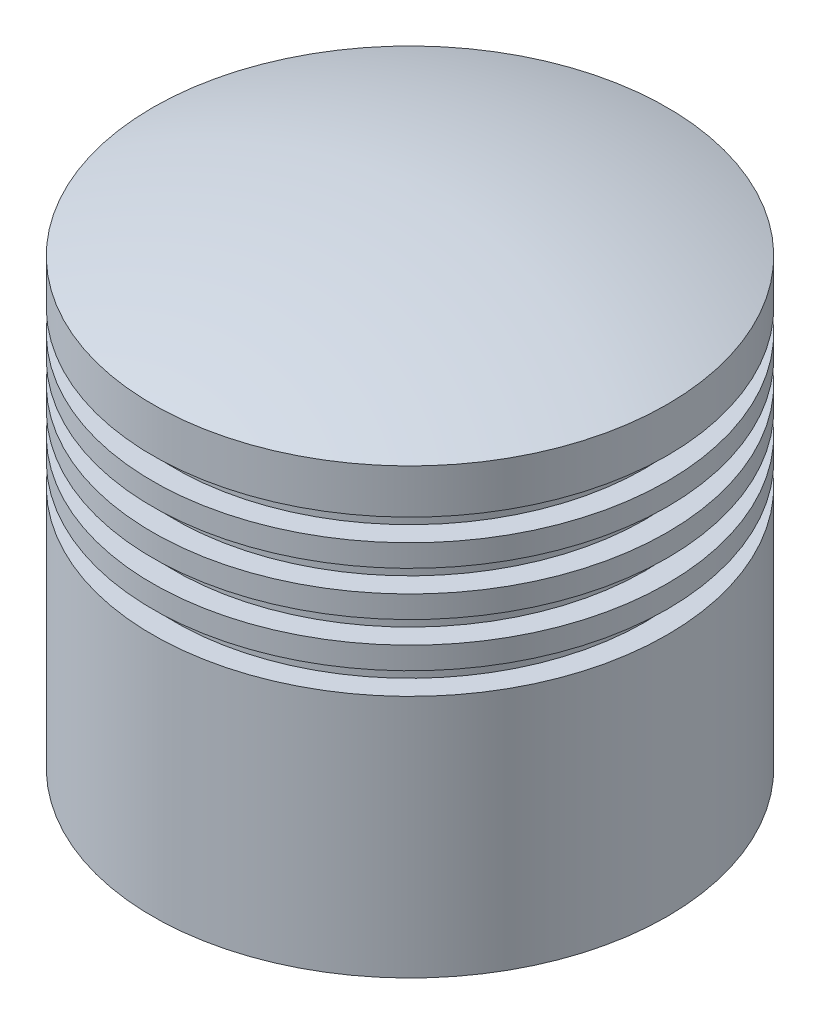
SolidWorks part; units mm, degrees
ref_plane "Front Plane" through (0, 0, 0) normal (0, 0, 1) x (1, 0, 0)
ref_plane "Top Plane" through (0, 0, 0) normal (0, 1, 0) x (1, 0, 0)
ref_plane "Right Plane" through (0, 0, 0) normal (1, 0, 0) x (0, 0, -1)
sketch "Sketch1" plane through (0, 0, 0) normal (0, 0, 1) x (1, 0, 0)
  line L0 (0, 0) -> (0, -10392.4106) construction
  line L1 (0, 0) -> (-10392.4106, 0) construction
  line L2 (50, 0) -> (58, 0)
  line L3 (58, 0) -> (58, 55)
  line L4 (58, 55) -> (53, 55)
  line L5 (53, 55) -> (53, 60)
  line L6 (53, 60) -> (58, 60)
  line L7 (58, 60) -> (58, 65)
  line L8 (58, 65) -> (53, 65)
  line L9 (53, 65) -> (53, 70)
  line L10 (53, 70) -> (58, 70)
  line L11 (58, 70) -> (58, 75)
  line L12 (58, 75) -> (53, 75)
  line L13 (53, 75) -> (53, 80)
  line L14 (53, 80) -> (58, 80)
  line L15 (58, 80) -> (58, 85)
  line L16 (58, 85) -> (53, 85)
  line L17 (53, 85) -> (53, 90)
  line L18 (53, 90) -> (58, 90)
  line L19 (50, 0) -> (50, 30)
  line L20 (50, 30) -> (43, 30)
  line L21 (43, 30) -> (43, 97.4261)
  line L22 (58, 90) -> (58, 100)
  line L23 (0, 110.2001) -> (0, 103.2001)
  arc A0 (43, 97.4261) -> (0, 103.2001) centre (0, -59.7999) ccw
  arc A1 (58, 100) -> (0, 110.2001) centre (0, -59.7999) ccw
  dimension "D7" = 86
  dimension "D8" = 163
  dimension "D9" = 170
  dimension "D1" = 8
  dimension "D2" = 5
  dimension "D3" = 7
  dimension "D4" = 30
  dimension "D5" = 90
  dimension "D6" = 100
revolve "Revolve1" add sketch "Sketch1" angle 360 about L0
